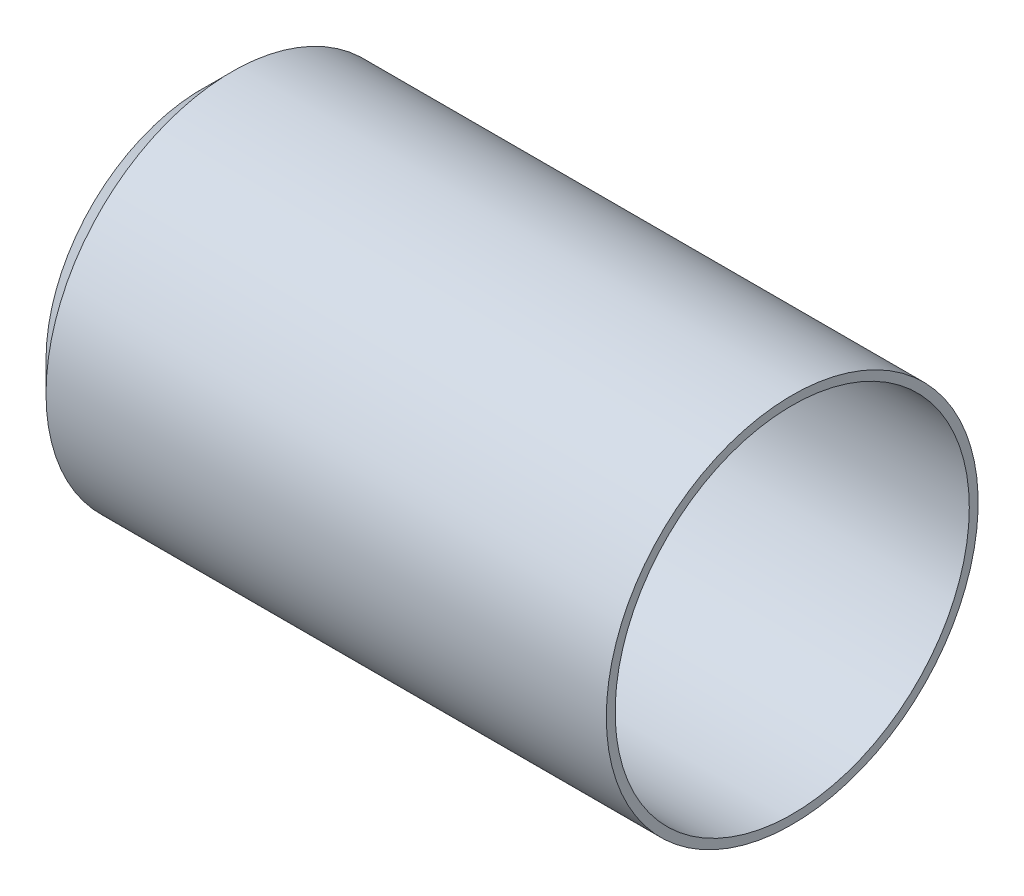
SolidWorks part; units mm, degrees
ref_plane "Front Plane" through (0, 0, 0) normal (0, 0, 1) x (1, 0, 0)
ref_plane "Top Plane" through (0, 0, 0) normal (0, 1, 0) x (1, 0, 0)
ref_plane "Right Plane" through (0, 0, 0) normal (1, 0, 0) x (0, 0, -1)
sketch "Sketch1" plane through (0, 0, 0) normal (1, 0, 0) x (0, 0, -1)
  circle A0 centre (0, 0) radius 31.525
  dimension "D1" = 63.05
extrude "Boss-Extrude1" add sketch "Sketch1" along normal blind 100
sketch "Sketch3" plane through (100, 0, 0) normal (1, 0, 0) x (0, 0, -1)
  circle A0 centre (0, 0) radius 30.025
  dimension "D1" = 60.05
extrude "Cut-Extrude1" cut sketch "Sketch3" against normal blind 95
chamfer "Chamfer2" distance 5 angle 45 1 edges at (0, 0, -31.525)
